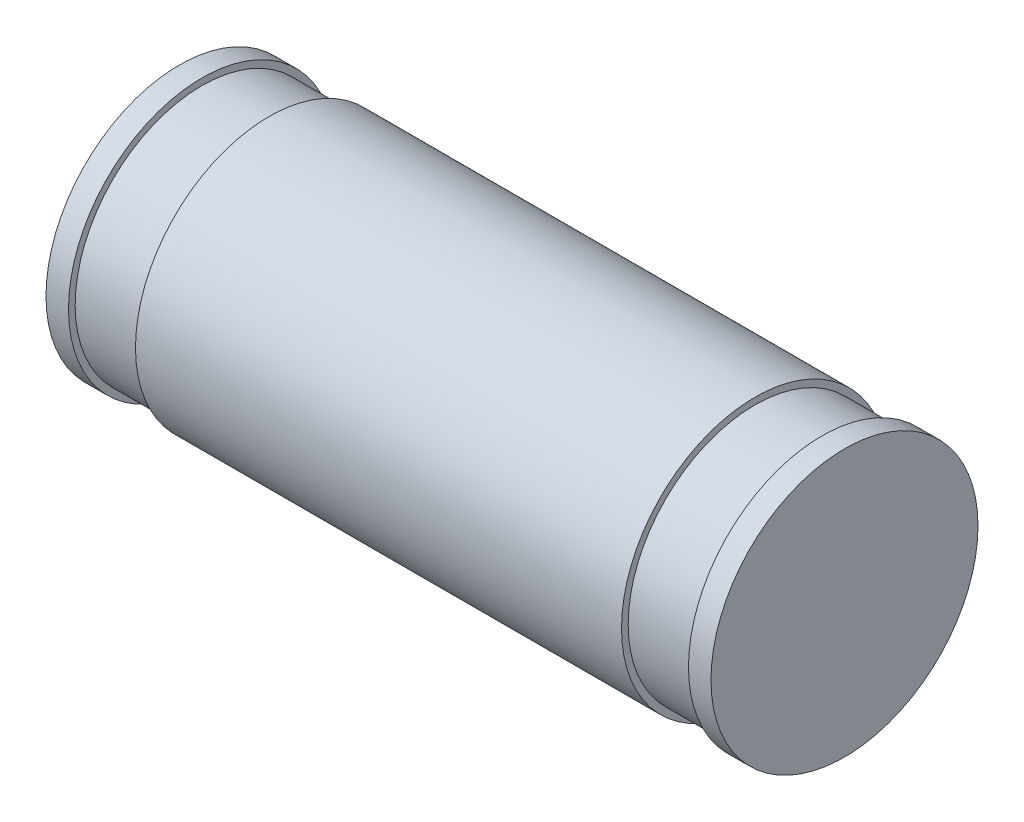
SolidWorks part; units mm, degrees
ref_plane "Front Plane" through (0, 0, 0) normal (0, 0, 1) x (1, 0, 0)
ref_plane "Top Plane" through (0, 0, 0) normal (0, 1, 0) x (1, 0, 0)
ref_plane "Right Plane" through (0, 0, 0) normal (1, 0, 0) x (0, 0, -1)
sketch "Sketch1" plane through (0, 0, 0) normal (0, 1, 0) x (1, 0, 0)
  line L0 (-55, 0) -> (55, 0) construction
  line L2 (8.874, 0) -> (8.874, 4)
  line L3 (8.874, 4) -> (8.2, 4)
  line L4 (-11.049, 0) -> (-11.049, 4)
  line L5 (-0.7167, 0) -> (-0.7167, 11.0956) construction
  line L11 (8.874, 0) -> (-11.049, 0)
  line L12 (-8.3684, 4) -> (6.1934, 4)
  line L13 (7.35, -1005.9685) -> (7.35, 0) construction
  line L14 (0, 4) -> (0, 5.95) construction
  line L15 (0, 5.95) -> (1, 5.95) construction
  line L16 (1, 5.95) -> (1, 4) construction
  line L17 (0, -55) -> (0, 55) construction
  line L18 (6.1934, 4) -> (6.1934, 3.8)
  line L19 (6.1934, 3.8) -> (8.2, 3.8)
  line L20 (8.2, 3.8) -> (8.2, 4)
  line L21 (-10.375, 4) -> (-10.375, 3.8)
  line L22 (-10.375, 3.8) -> (-8.3684, 3.8)
  line L23 (-8.3684, 3.8) -> (-8.3684, 4)
  line L24 (-10.375, 3.9) -> (-9.525, 3.9) construction
  line L25 (8.2, 3.9) -> (7.35, 3.9) construction
  line L28 (-10.375, 4) -> (-11.049, 4)
  line L29 (-16.9655, 0) -> (-19.8032, 0) construction
  line L30 (-9.525, 0) -> (-9.525, 10.5299) construction
  line L31 (-9.525, 0) -> (-8.4493, 1007.4357) construction
  line L38 (7.35, 0) -> (7.35, 1006.3404) construction
  point P0 (0, 0)
  point P6 (0.5923, 0)
  dimension "D2" = 4
  dimension "D3" = 1.524
  dimension "D4" = 1
  dimension "D5" = 5.95
  dimension "D6" = 6.35
  dimension "D7" = 1.524
  dimension "D8" = 9.525
  dimension "D9" = 11.0956
  dimension "D11" = 0.85
  dimension "D12" = 2.0066
  dimension "D13" = 0.2
ref_axis "Axis1" through (12.0023, 0, 0) along (-1, 0, 0)
revolve "Revolve1" add sketch "Sketch1" angle 360 about axis through (12.0023, 0, 0) along (-1, 0, 0)
